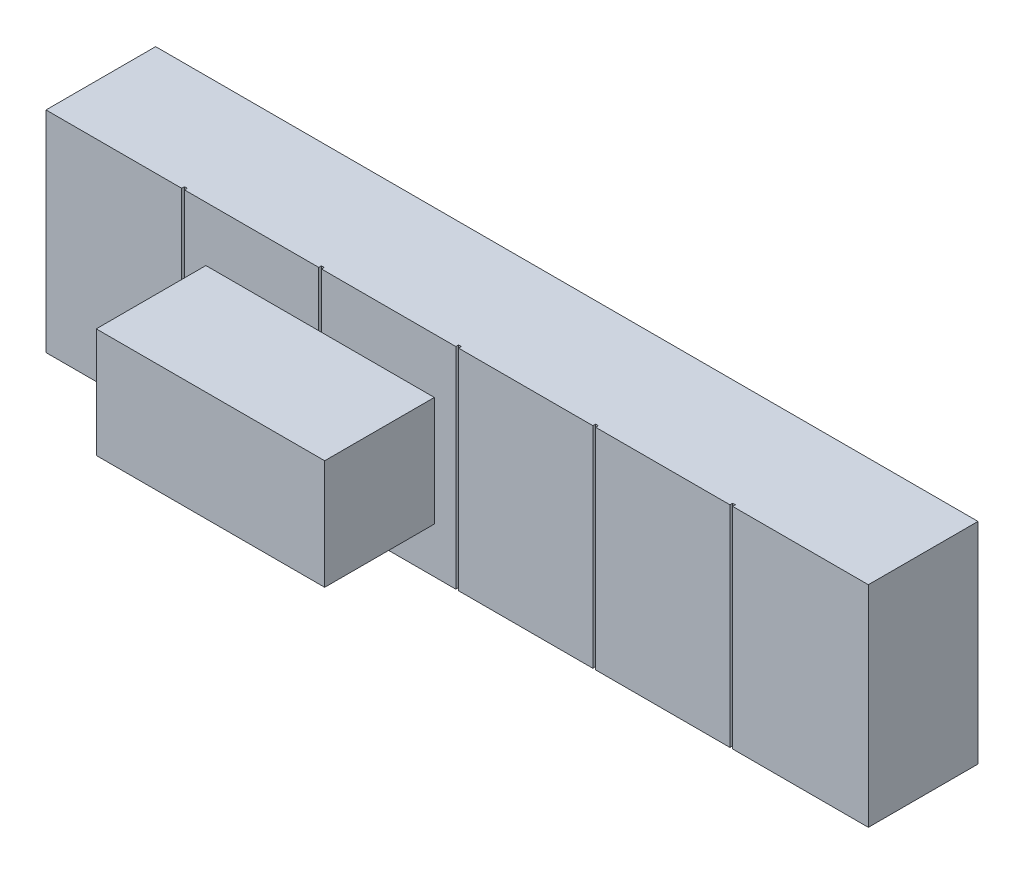
SolidWorks part; units mm, degrees
ref_plane "Front Plane" through (0, 0, 0) normal (0, 0, 1) x (1, 0, 0)
ref_plane "Top Plane" through (0, 0, 0) normal (0, 1, 0) x (1, 0, 0)
ref_plane "Right Plane" through (0, 0, 0) normal (1, 0, 0) x (0, 0, -1)
sketch "Sketch1" plane through (0, 0, 0) normal (0, 0, 1) x (1, 0, 0)
  line L1 (-450, -115) -> (450, -115)
  line L2 (-450, -115) -> (-450, 115)
  line L3 (-450, 115) -> (450, 115)
  line L4 (450, -115) -> (450, 115)
  line L5 (-450, -115) -> (450, 115) construction
  line L6 (-450, 115) -> (450, -115) construction
  point P0 (0, 0)
  dimension "D1" = 230
  dimension "D2" = 900
extrude "Boss-Extrude1" add sketch "Sketch1" along normal blind 120
sketch "Sketch2" plane through (0, 0, 120) normal (0, 0, 1) x (1, 0, 0)
  line L0 (450, 115) -> (-450, 115) construction
  line L1 (-301.5, 115) -> (-298.5, 115)
  line L2 (-301.5, 115) -> (-301.5, -115)
  line L3 (-301.5, -115) -> (-298.5, -115)
  line L4 (-298.5, 115) -> (-298.5, -115)
  line L5 (-450, -115) -> (450, -115) construction
  line L6 (-300, 115) -> (-300, -115) construction
  line L7 (-450, 115) -> (-450, -115) construction
  line L8 (-148.5, 115) -> (-148.5, -115)
  line L9 (-151.5, -115) -> (-148.5, -115)
  line L10 (-151.5, 115) -> (-151.5, -115)
  line L11 (-151.5, 115) -> (-148.5, 115)
  line L12 (1.5, 115) -> (1.5, -115)
  line L13 (-1.5, -115) -> (1.5, -115)
  line L14 (-1.5, 115) -> (-1.5, -115)
  line L15 (-1.5, 115) -> (1.5, 115)
  line L16 (151.5, 115) -> (151.5, -115)
  line L17 (148.5, -115) -> (151.5, -115)
  line L18 (148.5, 115) -> (148.5, -115)
  line L19 (148.5, 115) -> (151.5, 115)
  line L20 (301.5, 115) -> (301.5, -115)
  line L21 (298.5, -115) -> (301.5, -115)
  line L22 (298.5, 115) -> (298.5, -115)
  line L23 (298.5, 115) -> (301.5, 115)
  dimension "D1" = 150
  dimension "D2" = 3
  dimension "D3" = 5
extrude "Cut-Extrude1" cut sketch "Sketch2" against normal blind 3
sketch "Sketch3" plane through (0, 0, 120) normal (0, 0, 1) x (1, 0, 0)
  line L0 (-450, 115) -> (-450, -115) construction
  line L1 (-275, -65) -> (-25, -65)
  line L2 (-275, -65) -> (-275, 55)
  line L3 (-275, 55) -> (-25, 55)
  line L4 (-25, -65) -> (-25, 55)
  line L5 (-275, -65) -> (-25, 55) construction
  line L6 (-275, 55) -> (-25, -65) construction
  line L7 (-298.5, -115) -> (-151.5, -115) construction
  point P0 (-150, -5)
  dimension "D1" = 250
  dimension "D2" = 300
  dimension "D3" = 120
  dimension "D4" = 50
extrude "Boss-Extrude2" add sketch "Sketch3" along normal blind 120
